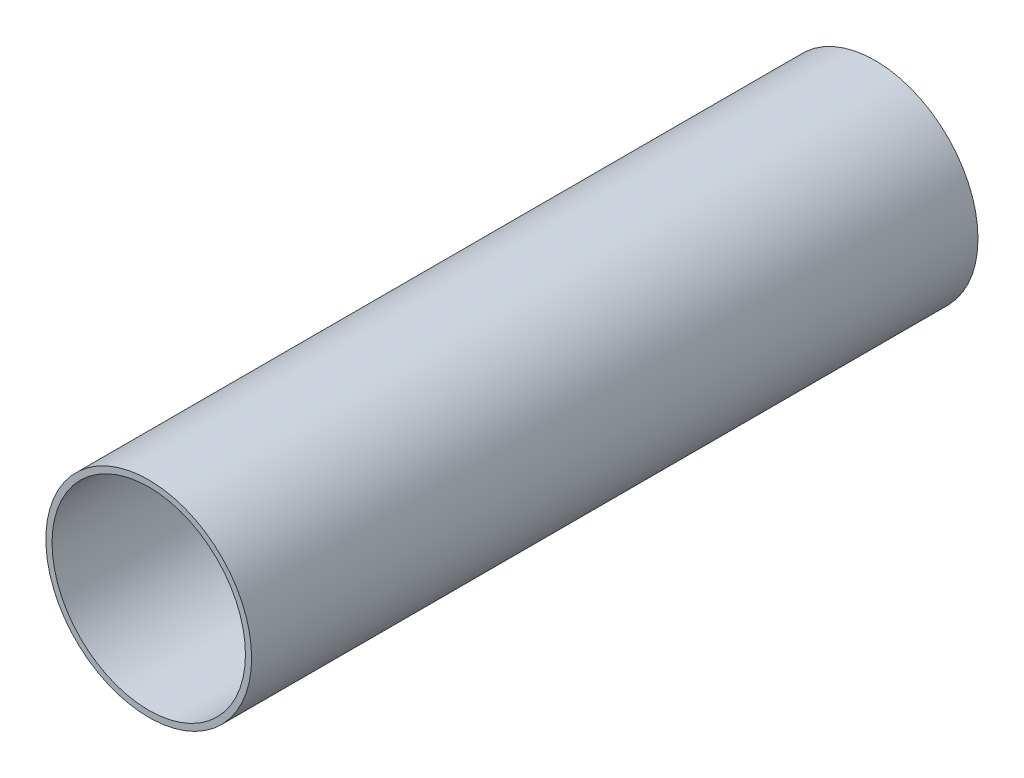
SolidWorks part; units mm, degrees
ref_plane "Спереди" through (0, 0, 0) normal (0, 0, 1) x (1, 0, 0)
ref_plane "Сверху" through (0, 0, 0) normal (0, 1, 0) x (1, 0, 0)
ref_plane "Справа" through (0, 0, 0) normal (1, 0, 0) x (0, 0, -1)
sketch "Эскиз1" plane through (0, 0, 0) normal (0, 0, 1) x (1, 0, 0)
  circle A0 centre (0, 0) radius 50
  dimension "D1" = 100
extrude "Бобышка-Вытянуть1" add sketch "Эскиз1" along normal blind 3
sketch "Эскиз2" plane through (0, 0, 3) normal (0, 0, 1) x (1, 0, 0)
  circle A0 centre (0, 0) radius 50
  circle A1 centre (0, 0) radius 47
  circle A2 centre (0, 0) radius 50 construction
  dimension "D1" = 3
extrude "Бобышка-Вытянуть2" add sketch "Эскиз2" along normal blind 350
sketch "Эскиз3" plane through (0, 0, 0) normal (0, 0, -1) x (-1, 0, 0)
  circle A0 centre (0, 0) radius 3
  dimension "D1" = 6
extrude "Вырез-Вытянуть1" cut sketch "Эскиз3" against normal blind 350
